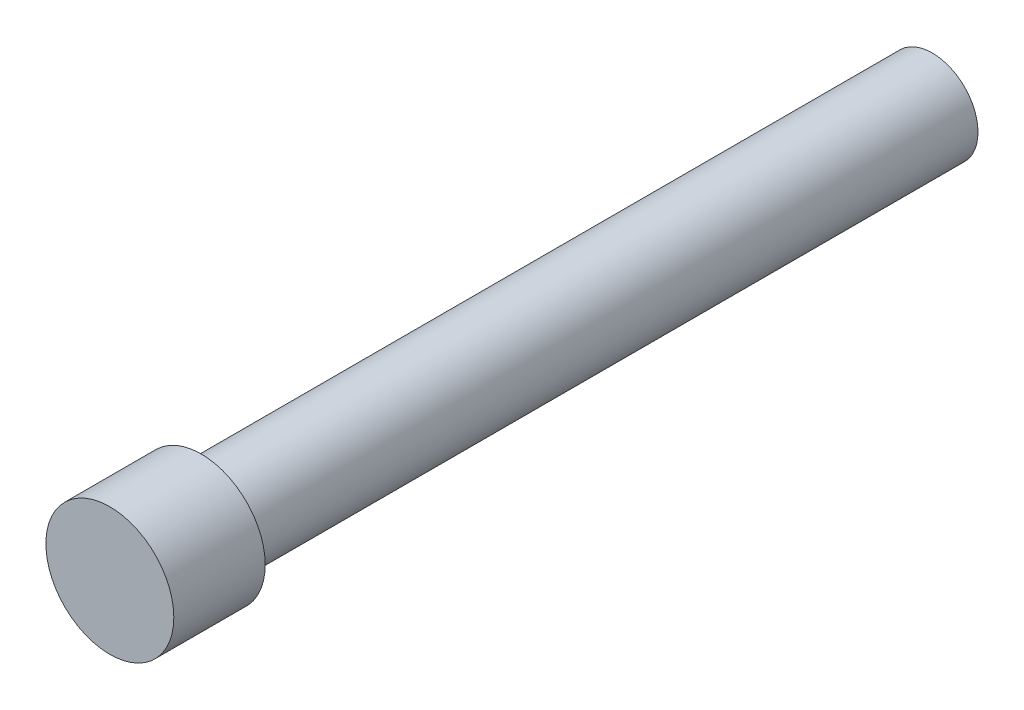
SolidWorks part; units mm, degrees
ref_plane "Front Plane" through (0, 0, 0) normal (0, 0, 1) x (1, 0, 0)
ref_plane "Top Plane" through (0, 0, 0) normal (0, 1, 0) x (1, 0, 0)
ref_plane "Right Plane" through (0, 0, 0) normal (1, 0, 0) x (0, 0, -1)
sketch "Sketch1" plane through (0, 0, 0) normal (0, 0, 1) x (1, 0, 0)
  circle A0 centre (0, 0) radius 5
  dimension "D1" = 10
extrude "Boss-Extrude1" add sketch "Sketch1" along normal blind 80
sketch "Sketch2" plane through (0, 0, 80) normal (0, 0, 1) x (1, 0, 0)
  circle A0 centre (0, 0) radius 7
  dimension "D1" = 14
extrude "Boss-Extrude2" add sketch "Sketch2" along normal blind 10
